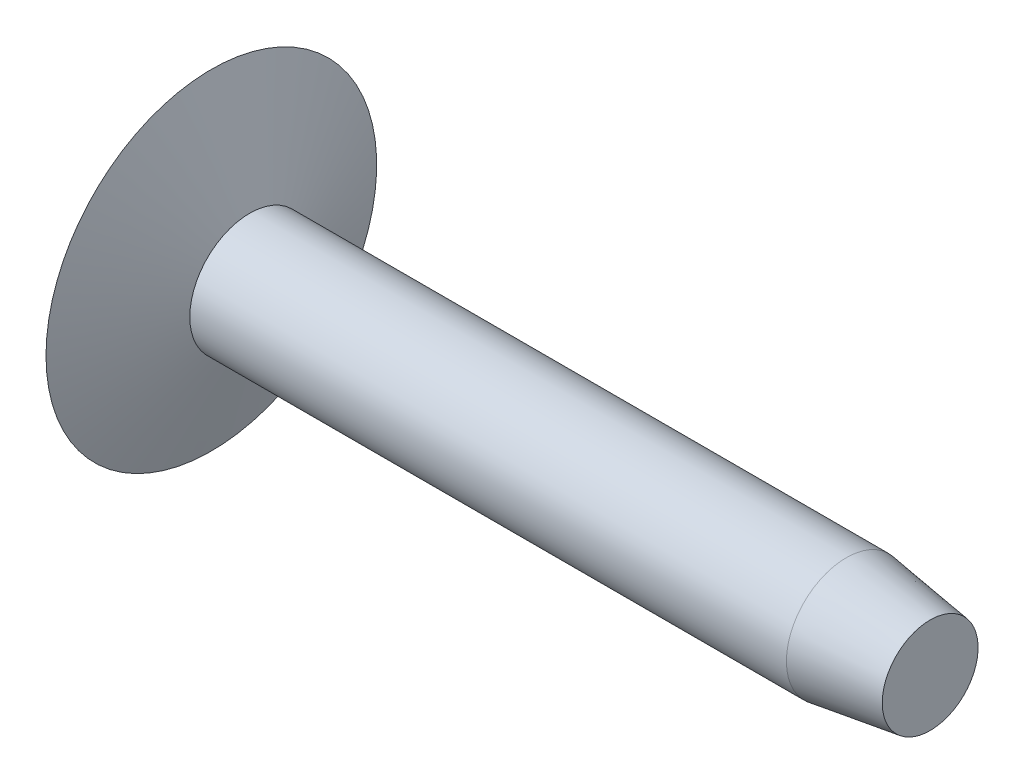
SolidWorks part; units mm, degrees
ref_plane "Plane1" through (0, 0, 0) normal (0, 0, 1) x (1, 0, 0)
ref_plane "Plane2" through (0, 0, 0) normal (0, 1, 0) x (1, 0, 0)
ref_plane "Plane3" through (0, 0, 0) normal (1, 0, 0) x (0, 0, -1)
sketch "Sketch1" plane through (0, 0, 0) normal (0, 0, 1) x (1, 0, 0)
  line L0 (0, 0) -> (45, 0) construction
  line L1 (0, 0) -> (0, 6.9)
  line L2 (0, 6.9) -> (1.6015, 2.5)
  line L3 (1.6015, 2.5) -> (26.5, 2.5)
  line L4 (26.5, 2.5) -> (30, 2)
  line L5 (30, 2) -> (30, 0)
  line L6 (30, 0) -> (0, 0)
  line L7 (0, -6.9) -> (1.6015, -2.5) construction
  dimension "D1" = 140
  dimension "Diameter" = 5
  dimension "PilotDia" = 4
  dimension "PilotLength" = 3.5
  dimension "HeadDia" = 13.8
  dimension "Length" = 30
revolve "Base-Revolve" add sketch "Sketch1" angle 360 about L0
